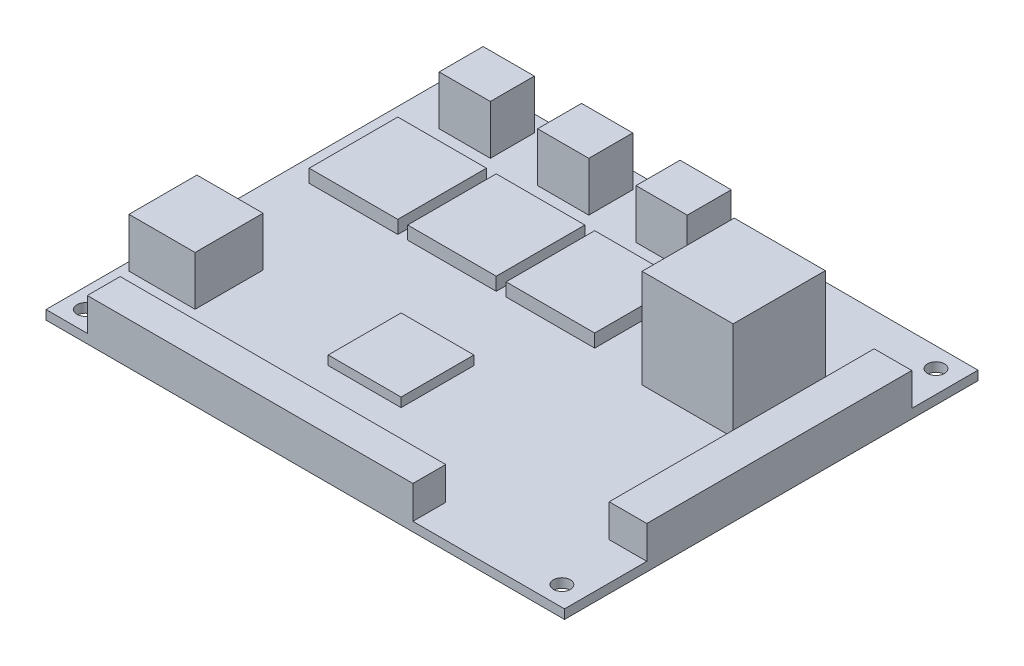
SolidWorks part; units mm, degrees
ref_plane "Front Plane" through (0, 0, 0) normal (0, 0, 1) x (1, 0, 0)
ref_plane "Top Plane" through (0, 0, 0) normal (0, 1, 0) x (1, 0, 0)
ref_plane "Right Plane" through (0, 0, 0) normal (1, 0, 0) x (0, 0, -1)
sketch "Sketch1" plane through (0, 0, 0) normal (0, 1, 0) x (1, 0, 0)
  line L1 (-50.165, 40.005) -> (50.165, 40.005)
  line L2 (-50.165, 40.005) -> (-50.165, -40.005)
  line L3 (-50.165, -40.005) -> (50.165, -40.005)
  line L4 (50.165, 40.005) -> (50.165, -40.005)
  line L5 (-50.165, 40.005) -> (50.165, -40.005) construction
  line L6 (-50.165, -40.005) -> (50.165, 40.005) construction
  point P0 (0, 0)
  dimension "D1" = 100.33
  dimension "D2" = 80.01
extrude "Boss-Extrude1" add sketch "Sketch1" along normal blind 1.778
hole_wizard "#4 Clearance Hole1" positions "Sketch3" profile "Sketch2" hole size "#4" standard "ANSI Inch"
sketch "Sketch3" plane through (0, 1.778, 0) normal (0, 1, 0) x (1, 0, 0)
  line L1 (-46.355, 36.195) -> (45.847, 36.195) construction
  line L2 (-46.355, 36.195) -> (-46.355, -36.195) construction
  line L3 (-46.355, -36.195) -> (45.847, -36.195) construction
  line L4 (45.847, 36.195) -> (45.847, -36.195) construction
  line L9 (-50.165, 40.005) -> (-50.165, -40.005) construction
  line L10 (-50.165, -40.005) -> (50.165, -40.005) construction
  point P0 (-46.355, 36.195)
  point P1 (45.847, -36.195)
  point P64 (-46.355, -36.195)
  point P65 (45.847, 36.195)
  dimension "D1" = 3.81
  dimension "D2" = 3.81
  dimension "D3" = 76.2
  dimension "D4" = 96.012
sketch "Sketch2" plane through (-46.355, 1.778, -36.195) normal (1, 0, 0) x (0, 0, 1)
  line L0 (0, 0) -> (0, 13.6806)
  line L1 (0, 13.6806) -> (1.6319, 12.7)
  line L2 (1.6319, 12.7) -> (1.6319, 0)
  line L5 (1.6319, 0) -> (0, 0)
  line L10 (0, 13.6806) -> (-1.632, 12.7) construction
  line L11 (0, -6.35) -> (0, 107.95) construction
  dimension "Hole Dia." = 3.2639
  dimension "Hole Depth" = 12.7
  dimension "Drill Angle" = 118
sketch "Sketch4" plane through (0, 1.778, 0) normal (0, 1, 0) x (1, 0, 0)
  line L0 (-50.165, 40.005) -> (-50.165, -40.005) construction
  line L1 (-45.847, 23.749) -> (-28.702, 23.749)
  line L2 (-45.847, 23.749) -> (-45.847, 6.604)
  line L3 (-45.847, 6.604) -> (-28.702, 6.604)
  line L4 (-28.702, 23.749) -> (-28.702, 6.604)
  line L5 (-50.165, -40.005) -> (50.165, -40.005) construction
  dimension "D1" = 17.145
  dimension "D2" = 4.318
  dimension "D3" = 46.609
extrude "Boss-Extrude2" add sketch "Sketch4" along normal blind 2.54
sketch "Sketch6" plane through (0, 1.778, 0) normal (0, 1, 0) x (1, 0, 0)
  line L0 (-50.165, 40.005) -> (-50.165, -40.005) construction
  line L1 (-42.418, 36.83) -> (-32.512, 36.83)
  line L2 (-42.418, 36.83) -> (-42.418, 28.321)
  line L3 (-42.418, 28.321) -> (-32.512, 28.321)
  line L4 (-32.512, 36.83) -> (-32.512, 28.321)
  line L5 (-50.165, -40.005) -> (50.165, -40.005) construction
  dimension "D1" = 9.906
  dimension "D2" = 7.747
  dimension "D3" = 8.509
  dimension "D4" = 68.326
extrude "Boss-Extrude3" add sketch "Sketch6" along normal blind 9.525
pattern_linear "LPattern1" count 3 spacing 19.05 along (1, 0, 0) of "Boss-Extrude2", "Boss-Extrude3"
sketch "Sketch7" plane through (0, 1.778, 0) normal (0, 1, 0) x (1, 0, 0)
  line L0 (-50.165, 40.005) -> (-50.165, -40.005) construction
  line L1 (-13.462, -8.001) -> (0.635, -8.001)
  line L2 (-13.462, -8.001) -> (-13.462, -22.098)
  line L3 (-13.462, -22.098) -> (0.635, -22.098)
  line L4 (0.635, -8.001) -> (0.635, -22.098)
  line L5 (-50.165, -40.005) -> (50.165, -40.005) construction
  dimension "D1" = 14.097
  dimension "D2" = 14.097
  dimension "D3" = 36.703
  dimension "D4" = 17.907
extrude "Boss-Extrude4" add sketch "Sketch7" along normal blind 1.778
sketch "Sketch8" plane through (0, 1.778, 0) normal (0, 1, 0) x (1, 0, 0)
  line L0 (-50.165, -40.005) -> (50.165, -40.005) construction
  line L1 (-42.164, -33.655) -> (20.828, -33.655)
  line L2 (-42.164, -33.655) -> (-42.164, -40.005)
  line L3 (-42.164, -40.005) -> (20.828, -40.005)
  line L4 (20.828, -33.655) -> (20.828, -40.005)
  line L5 (-50.165, 40.005) -> (-50.165, -40.005) construction
  dimension "D1" = 8.001
  dimension "D2" = 70.993
  dimension "D3" = 6.35
extrude "Boss-Extrude5" add sketch "Sketch8" along normal blind 6.35
sketch "Sketch9" plane through (0, 1.778, 0) normal (0, 1, 0) x (1, 0, 0)
  line L0 (50.165, -40.005) -> (50.165, 40.005) construction
  line L1 (50.165, 27.1883) -> (42.8946, 27.1883)
  line L2 (50.165, 27.1883) -> (50.165, -24.0831)
  line L3 (50.165, -24.0831) -> (42.8946, -24.0831)
  line L4 (42.8946, 27.1883) -> (42.8946, -24.0831)
extrude "Boss-Extrude6" add sketch "Sketch9" along normal blind 6.35
sketch "Sketch10" plane through (0, 1.778, 0) normal (0, 1, 0) x (1, 0, 0)
  line L1 (20.1475, 22.8555) -> (37.7675, 22.8555)
  line L2 (20.1475, 22.8555) -> (20.1475, 5.0188)
  line L3 (20.1475, 5.0188) -> (37.7675, 5.0188)
  line L4 (37.7675, 22.8555) -> (37.7675, 5.0188)
extrude "Boss-Extrude7" add sketch "Sketch10" along normal blind 19.05
sketch "Sketch11" plane through (0, 1.778, 0) normal (0, 1, 0) x (1, 0, 0)
  line L1 (-48.5687, -12.3951) -> (-35.776, -12.3951)
  line L2 (-48.5687, -12.3951) -> (-48.5687, -25.5491)
  line L3 (-48.5687, -25.5491) -> (-35.776, -25.5491)
  line L4 (-35.776, -12.3951) -> (-35.776, -25.5491)
extrude "Boss-Extrude8" add sketch "Sketch11" along normal blind 9.525
